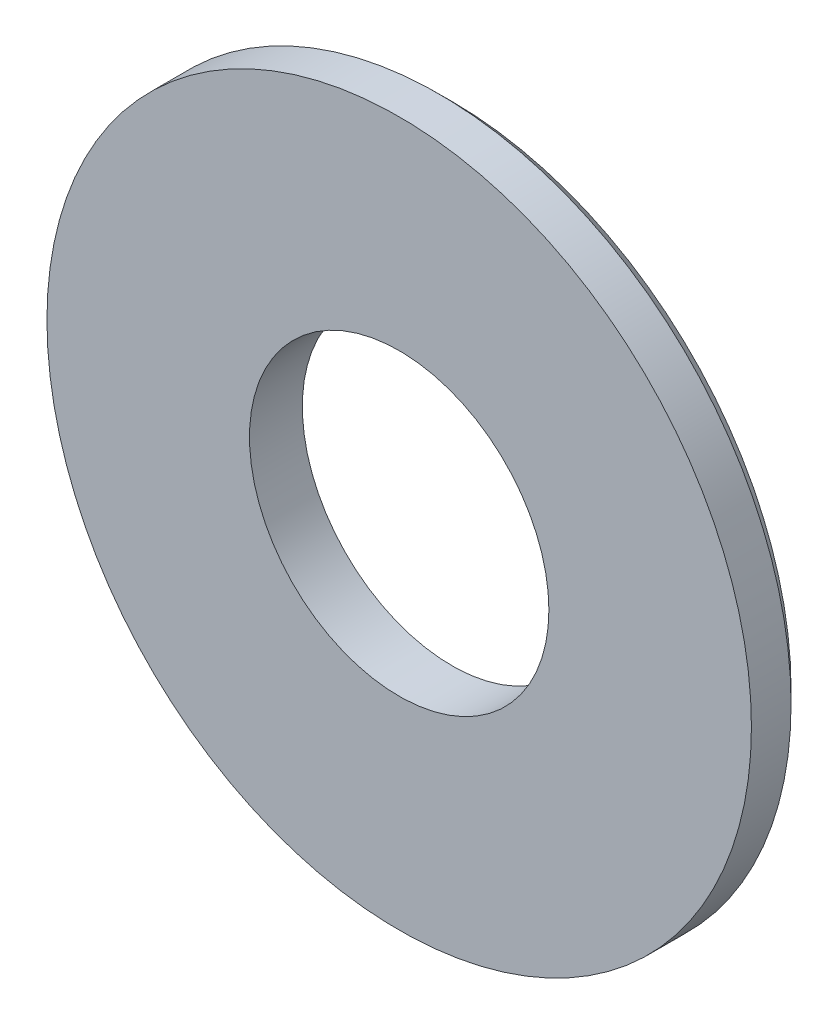
SolidWorks part; units mm, degrees
ref_plane "Přední rovina" through (0, 0, 0) normal (0, 0, 1) x (1, 0, 0)
ref_plane "Vrchní rovina" through (0, 0, 0) normal (0, 1, 0) x (1, 0, 0)
ref_plane "Pravá rovina" through (0, 0, 0) normal (1, 0, 0) x (0, 0, -1)
sketch "Skica1" plane through (0, 0, 0) normal (0, 0, 1) x (1, 0, 0)
  circle A0 centre (0, 0) radius 0.85
  circle A1 centre (0, 0) radius 2
  dimension "d1" = 1.7
  dimension "d2" = 4
extrude "Vysunout1" add sketch "Skica1" along normal blind 0.3
chamfer "Zkosit1" distance 0.075 angle 45 1 edges at (2, 0, 0)
equation "\"0,25*h@Zkosit1\" = 0.25 * \"H@Vysunout1\""
